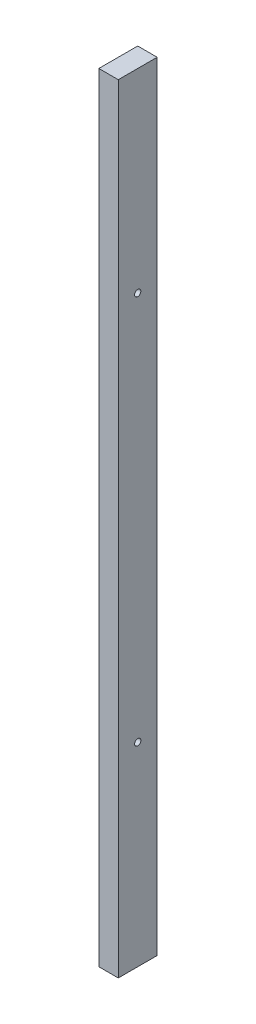
SolidWorks part; units mm, degrees
ref_plane "Спереди" through (0, 0, 0) normal (0, 0, 1) x (1, 0, 0)
ref_plane "Сверху" through (0, 0, 0) normal (0, 1, 0) x (1, 0, 0)
ref_plane "Справа" through (0, 0, 0) normal (1, 0, 0) x (0, 0, -1)
other "Configuration Table"
sketch "Эскиз1" plane through (0, 0, 0) normal (0, 1, 0) x (1, 0, 0)
  line L1 (12.5, 25) -> (-12.5, 25)
  line L2 (12.5, 25) -> (12.5, -25)
  line L3 (12.5, -25) -> (-12.5, -25)
  line L4 (-12.5, 25) -> (-12.5, -25)
  line L5 (12.5, 25) -> (-12.5, -25) construction
  line L6 (12.5, -25) -> (-12.5, 25) construction
  point P0 (0, 0)
extrude "Бобышка-Вытянуть1" add sketch "Эскиз1" along normal blind 1000
sketch "Эскиз2" plane through (12.5, 0, 0) normal (1, 0, 0) x (0, 0, -1)
  line L0 (0, 1000) -> (0, 0) construction
  line L1 (-25, 1000) -> (25, 1000) construction
  line L2 (0, 0) -> (0, 500) construction
  line L3 (0, 1000) -> (0, 500) construction
  circle A0 centre (0, 250) radius 4
  circle A1 centre (0, 750) radius 4
extrude "Вырез-Вытянуть1" cut sketch "Эскиз2" against normal blind 2214.159
